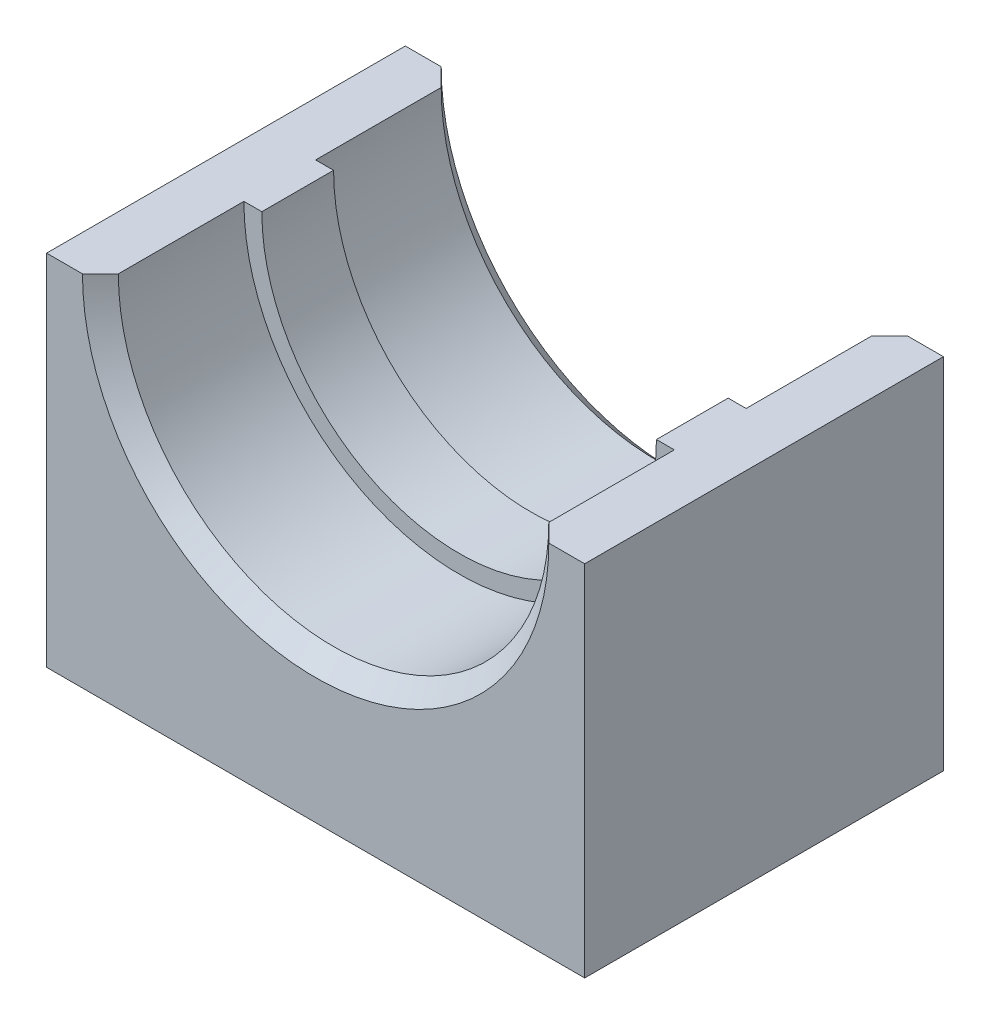
SolidWorks part; units mm, degrees
ref_plane "정면" through (0, 0, 0) normal (0, 0, 1) x (1, 0, 0)
ref_plane "윗면" through (0, 0, 0) normal (0, 1, 0) x (1, 0, 0)
ref_plane "우측면" through (0, 0, 0) normal (1, 0, 0) x (0, 0, -1)
sketch "스케치1" plane through (0, 0, 0) normal (0, 0, 1) x (1, 0, 0)
  line L1 (-15, -10) -> (15, -10)
  line L2 (-15, -10) -> (-15, 10)
  line L3 (-15, 10) -> (15, 10)
  line L4 (15, -10) -> (15, 10)
  line L5 (-15, -10) -> (15, 10) construction
  line L6 (-15, 10) -> (15, -10) construction
  point P0 (0, 0)
  dimension "D1" = 20
  dimension "D2" = 30
extrude "보스-돌출1" add sketch "스케치1" along normal mid plane 20 contours L3 L4 L1 L2
sketch "스케치2" plane through (0, 0, 10) normal (0, 0, 1) x (1, 0, 0)
  line L0 (-15, 10) -> (15, 10) construction
  circle A0 centre (0, 10) radius 12
  dimension "D1" = 24
extrude "컷-돌출1" cut sketch "스케치2" against normal blind 8
mirror "대칭 복사1" about plane through (0, 0, 0) normal (0, 0, 1) of "컷-돌출1"
sketch "스케치3" plane through (0, 0, 2) normal (0, 0, 1) x (1, 0, 0)
  line L0 (-12, 10) -> (12, 10) construction
  circle A0 centre (0, 10) radius 11
  dimension "D1" = 22
extrude "컷-돌출2" cut sketch "스케치3" against normal blind 10 contours A0
chamfer "모따기1" distance 1 angle 45 2 edges at (0, -2, -10) (0, -2, 10)
